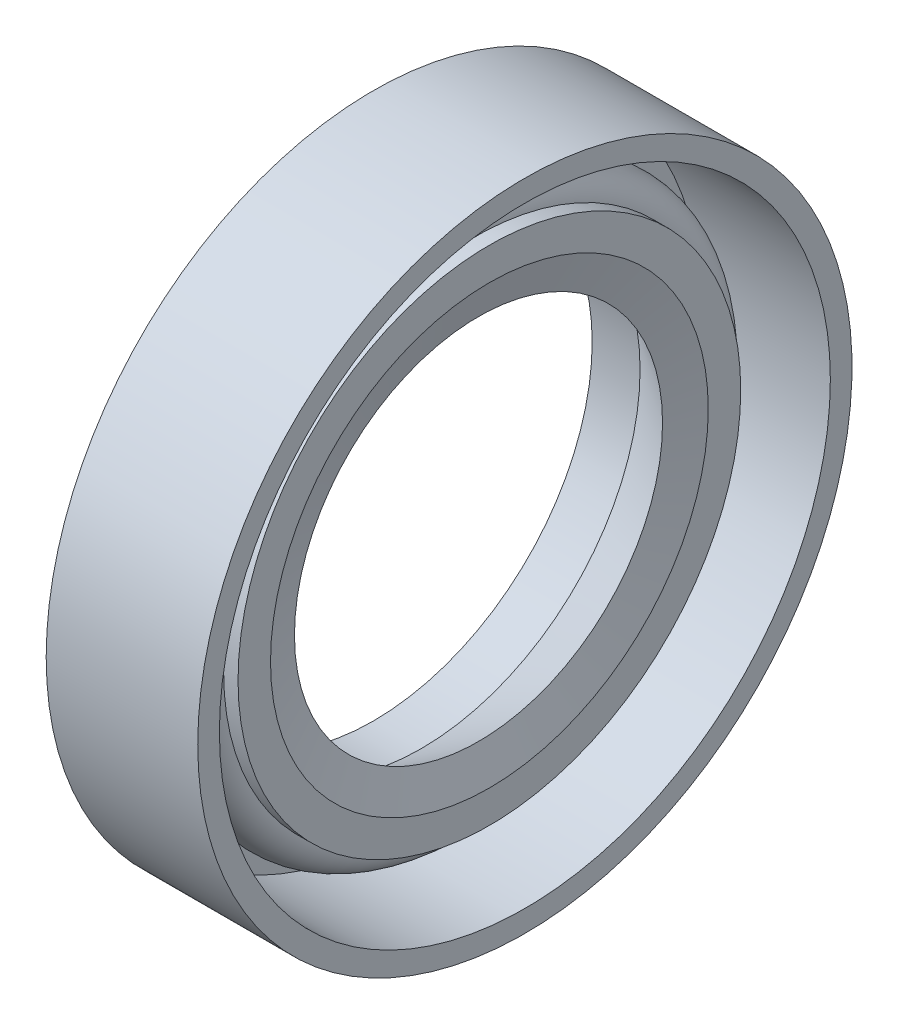
SolidWorks part; units mm, degrees
material "VITON"
ref_plane "Ebene vorne" through (0, 0, 0) normal (0, 0, 1) x (1, 0, 0)
ref_plane "Ebene oben" through (0, 0, 0) normal (0, 1, 0) x (1, 0, 0)
ref_plane "Ebene rechts" through (0, 0, 0) normal (1, 0, 0) x (0, 0, -1)
sketch "Sketch1" plane through (0, 0, 0) normal (0, 0, 1) x (1, 0, 0)
  line L1 (0, 15.1087) -> (7, 15.1087)
  line L2 (7, 15.1087) -> (7, 14.1087)
  line L3 (7, 14.1087) -> (1, 14.1087)
  line L4 (1, 14.1087) -> (1, 11.6087)
  line L5 (1, 11.6087) -> (2.2122, 11.6087)
  line L6 (4.6956, 11.6087) -> (5.3608, 11.6087)
  line L7 (5.3608, 11.6087) -> (5.3608, 10.1087)
  line L8 (5.3608, 10.1087) -> (4.8582, 8.5)
  line L9 (4.8582, 8.5) -> (2.2122, 10.1087)
  line L10 (2.2122, 10.1087) -> (0, 10.1087)
  line L11 (0, 10.1087) -> (0, 15.1087)
  line L12 (0, 0) -> (7.4538, 0) construction
  arc A0 (2.2122, 11.6087) -> (4.6956, 11.6087) centre (3.4539, 11.6087) cw
  dimension "D1" = 5
  dimension "D2" = 2.5
  dimension "D3" = 1
  dimension "D4" = 7
  dimension "D5" = 1
  dimension "D6" = 1.5
  dimension "D7" = 8.5
revolve "Revolve1" add sketch "Sketch1" angle 360 about L12
